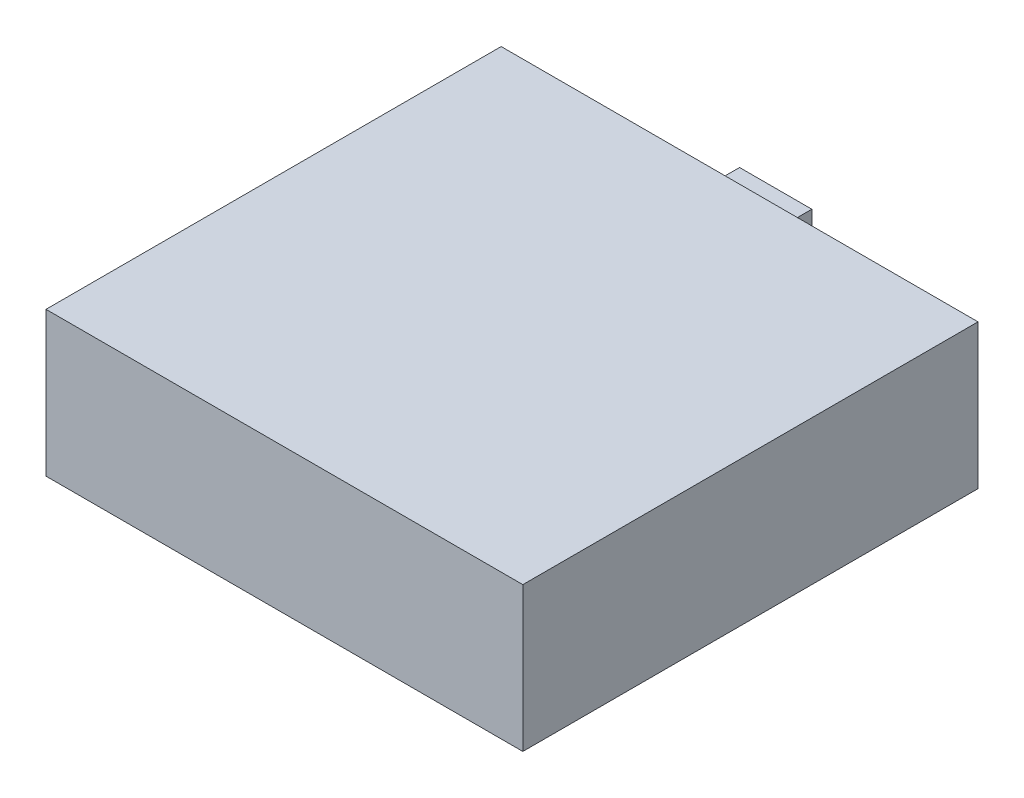
SolidWorks part; units mm, degrees
ref_plane "Front Plane" through (0, 0, 0) normal (0, 0, 1) x (1, 0, 0)
ref_plane "Top Plane" through (0, 0, 0) normal (0, 1, 0) x (1, 0, 0)
ref_plane "Right Plane" through (0, 0, 0) normal (1, 0, 0) x (0, 0, -1)
sketch "Sketch1" plane through (0, 0, 0) normal (0, 1, 0) x (1, 0, 0)
  line L1 (-33, 31.5) -> (33, 31.5)
  line L2 (-33, 31.5) -> (-33, -31.5)
  line L3 (-33, -31.5) -> (33, -31.5)
  line L4 (33, 31.5) -> (33, -31.5)
  line L5 (-33, 31.5) -> (33, -31.5) construction
  line L6 (-33, -31.5) -> (33, 31.5) construction
  point P0 (0, 0)
  dimension "D1" = 63
  dimension "D2" = 66
extrude "Boss-Extrude1" add sketch "Sketch1" along normal blind 20
sketch "Sketch2" plane through (0, 0, -31.5) normal (0, 0, -1) x (-1, 0, 0)
  line L1 (-5, 17) -> (5, 17)
  line L2 (-5, 17) -> (-5, 13)
  line L3 (-5, 13) -> (5, 13)
  line L4 (5, 17) -> (5, 13)
  line L5 (-5, 17) -> (5, 13) construction
  line L6 (-5, 13) -> (5, 17) construction
  point P0 (0, 15)
  dimension "D1" = 4
  dimension "D2" = 10
  dimension "D3" = 15
extrude "Boss-Extrude2" add sketch "Sketch2" along normal blind 5
